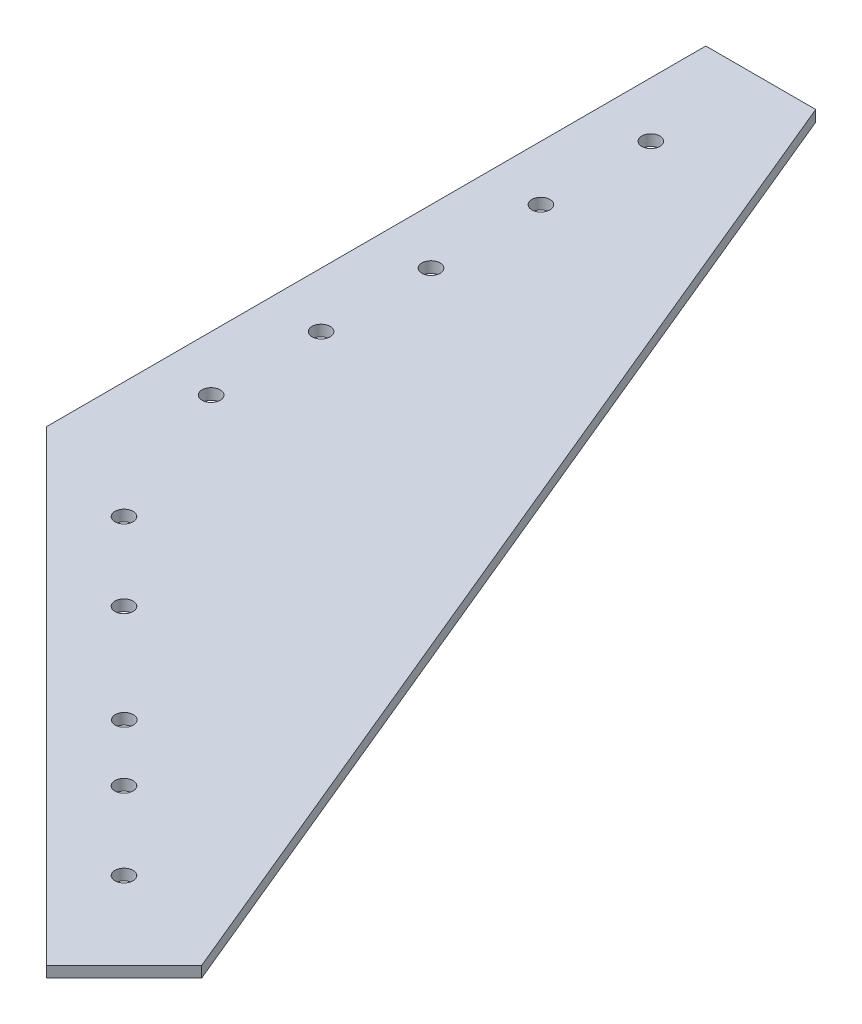
SolidWorks part; units mm, degrees
ref_plane "Front" through (0, 0, 0) normal (0, 0, 1) x (1, 0, 0)
ref_plane "Top" through (0, 0, 0) normal (0, 1, 0) x (1, 0, 0)
ref_plane "Right" through (0, 0, 0) normal (1, 0, 0) x (0, 0, -1)
sketch "Sketch1" plane through (0, 0, 0) normal (0, 1, 0) x (1, 0, 0)
  line L0 (0, 0) -> (0, -152.4)
  line L2 (0, 0) -> (25.4, 0)
  line L5 (0, -152.4) -> (107.7631, -260.1631)
  line L6 (107.7631, -260.1631) -> (125.7236, -242.2026)
  line L7 (25.4, 0) -> (125.7236, -242.2026)
  dimension "D1" = 152.4
  dimension "D2" = 25.4
  dimension "D3" = 135
  dimension "D4" = 152.4
extrude "Boss-Extrude1" add sketch "Sketch1" along normal blind 2.54
hole_wizard "#8 (0.199) Diameter Hole1" positions "Sketch4" profile "Sketch5" hole size "#8" standard "ANSI Inch" end condition through all
sketch "Sketch4" plane through (0, 2.54, 0) normal (0, 1, 0) x (1, 0, 0)
  arc A0 (28.4574, -162.7892) -> (25.5319, -159.8636) centre (26.9408, -161.3803) ccw construction
  arc A1 (46.418, -180.7497) -> (43.4924, -177.8241) centre (44.9013, -179.3408) ccw construction
  arc A3 (82.339, -216.6707) -> (79.4134, -213.7451) centre (80.8223, -215.2618) ccw construction
  arc A4 (100.2995, -234.6312) -> (97.3739, -231.7056) centre (98.7828, -233.2223) ccw construction
  point P2 (12.7, -25.4)
  point P5 (12.7, -50.8)
  point P8 (12.7, -76.2)
  point P11 (12.7, -101.6)
  point P14 (12.7, -127)
  point P17 (26.9408, -161.3803)
  point P19 (44.9013, -179.3408)
  point P21 (67.6551, -202.0315)
  point P23 (80.8223, -215.2618)
  point P25 (98.7828, -233.2223)
sketch "Sketch5" plane through (12.7, 2.54, 25.4) normal (1, 0, 0) x (0, 0, 1)
  line L0 (0, 0) -> (0, 2.54)
  line L1 (0, 2.54) -> (2.0955, 2.54)
  line L2 (2.0955, 2.54) -> (2.0955, 0)
  line L5 (2.0955, 0) -> (0, 0)
  line L11 (0, -6.35) -> (0, 107.95) construction
  dimension "Thru Hole Dia." = 4.191
  dimension "Thru Hole Depth" = 2.54
